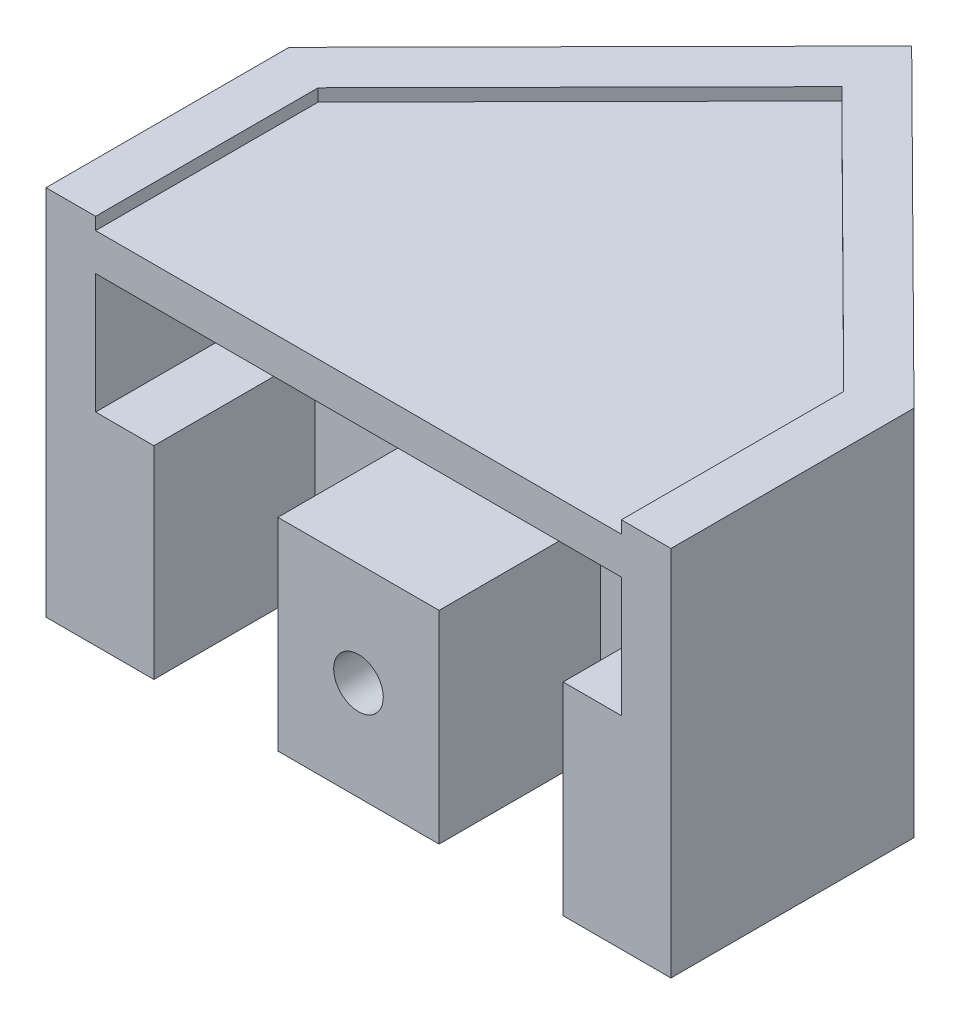
SolidWorks part; units mm, degrees
ref_plane "Plan de face" through (0, 0, 0) normal (0, 0, 1) x (1, 0, 0)
ref_plane "Plan de dessus" through (0, 0, 0) normal (0, 1, 0) x (1, 0, 0)
ref_plane "Plan de droite" through (0, 0, 0) normal (1, 0, 0) x (0, 0, -1)
sketch "Sketch2" plane through (0, 0, 0) normal (0, 0, 1) x (1, 0, 0)
  line L1 (0, 0) -> (-25.2, 0)
  line L2 (0, 0) -> (0, 15)
  line L3 (0, 15) -> (-25.2, 15)
  line L4 (-25.2, 0) -> (-25.2, 15)
  dimension "D1" = 25.2
  dimension "D2" = 15
extrude "Boss-Extrude2" add sketch "Sketch2" along normal blind 2
sketch "Sketch3" plane through (0, 0, 2) normal (0, 0, 1) x (1, 0, 0)
  line L0 (0, 15) -> (-25.2, 15) construction
  line L1 (-25.2, 0) -> (-23.2, 0)
  line L2 (-25.2, 0) -> (-25.2, 15)
  line L3 (-25.2, 15) -> (-23.2, 15)
  line L4 (-23.2, 0) -> (-23.2, 15)
  line L6 (-23.2, 13) -> (0, 13)
  line L7 (-23.2, 13) -> (-23.2, 15)
  line L8 (-23.2, 15) -> (0, 15)
  line L9 (0, 13) -> (0, 15)
  line L10 (0, 0) -> (-2, 0)
  line L11 (0, 0) -> (0, 13)
  line L12 (0, 13) -> (-2, 13)
  line L13 (-2, 0) -> (-2, 13)
  line M4 (0, 0) -> (0, 15)
  line M5 (0, 15) -> (-25.2, 15)
  line M6 (-25.2, 15) -> (-25.2, 0)
  line M7 (-25.2, 0) -> (0, 0)
  dimension "D1" = 2
  dimension "D2" = 2
  dimension "D3" = 2
extrude "Boss-Extrude3" add sketch "Sketch3" along normal blind 7.8 contours L4 M7 M5 M6 | L4 L6 M4 M5 | L13 L6 M7 M4
sketch "Sketch4" plane through (0, 15, 0) normal (0, 1, 0) x (1, 0, 0)
  line L0 (0, 0) -> (-12.6933, 12.5997) construction
  line L1 (-25.2, 0) -> (-12.6933, 12.5997) construction
  line L2 (0, 0) -> (-12.6933, 12.5997)
  line L3 (-12.6933, 12.5997) -> (-25.2, 0)
  line L4 (-25.2, 0) -> (0, 0)
extrude "Boss-Extrude4" add sketch "Sketch4" against normal through all
sketch "Sketch5" plane through (0, 0, 2) normal (0, 0, 1) x (1, 0, 0)
  line L0 (-23.2, 0) -> (-2, 0) construction
  line L1 (-20.85, 0) -> (-4.35, 0)
  line L2 (-20.85, 0) -> (-20.85, 8.1631)
  line L3 (-20.85, 8.1631) -> (-4.35, 8.1631)
  line L4 (-4.35, 0) -> (-4.35, 8.1631)
  line L5 (-20.1, 6) -> (-20.1, 8.5) construction
  line L7 (-2, 0) -> (-2, 13) construction
  line L8 (-23.2, 0) -> (-2, 0)
  line L9 (-23.2, 0) -> (-23.2, 8.1631)
  line L10 (-23.2, 8.1631) -> (-2, 8.1631)
  line L11 (-2, 0) -> (-2, 8.1631)
  line L12 (-17.6, 6) -> (-17.6, 8.5) construction
  line L13 (-15.85, 0) -> (-9.35, 0)
  line L14 (-15.85, 0) -> (-15.85, 8.1631)
  line L15 (-15.85, 8.1631) -> (-9.35, 8.1631)
  line L16 (-9.35, 0) -> (-9.35, 8.1631)
  line M7 (-23.2, 0) -> (-2, 0)
  line M8 (-2, 0) -> (-2, 13)
  line M10 (-23.2, 13) -> (-23.2, 0)
  dimension "D1" = 16.5
  dimension "D2" = 0.75
  dimension "D3" = 0
  dimension "D4" = 6.5
  dimension "D5" = 1.75
extrude "Boss-Extrude5" add sketch "Sketch5" along normal blind 7.8 contours L8 L16 L10 L14 | L10 L4 M7 M8 | L10 L2 M10 M7
sketch "Sketch6" plane through (0, 0, 2) normal (0, 0, 1) x (1, 0, 0)
  line L1 (-20.85, 0) -> (-15.85, 0)
  line L2 (-20.85, 0) -> (-20.85, 8.1631)
  line L3 (-20.85, 8.1631) -> (-15.85, 8.1631)
  line L4 (-15.85, 0) -> (-15.85, 8.1631)
  line L5 (-9.35, 0) -> (-4.35, 0)
  line L6 (-9.35, 0) -> (-9.35, 8.1631)
  line L7 (-9.35, 8.1631) -> (-4.35, 8.1631)
  line L8 (-4.35, 0) -> (-4.35, 8.1631)
extrude "Boss-Extrude6" add sketch "Sketch6" along normal blind 1.3
sketch "Sketch8" plane through (0, 15, 0) normal (0, 1, 0) x (1, 0, 0)
  line L6 (-23.2, -7.8) -> (-2, -7.8)
  line L7 (-23.2, -7.8) -> (-23.2, -9.8)
  line L8 (-23.2, -9.8) -> (-2, -9.8)
  line L9 (-2, -7.8) -> (-2, -9.8)
  line L10 (-2, -7.8) -> (-2, -0.8328)
  line L11 (-2, -0.8328) -> (-12.6829, 9.7712)
  line L12 (-12.6829, 9.7712) -> (-23.2, -0.8241)
  line L13 (-23.2, -0.8241) -> (-23.2, -7.8)
  line L14 (-23.2, -7.8) -> (-2, -7.8)
  line L15 (-2, -7.8) -> (-2, -0.8328)
  line L16 (-2, -0.8328) -> (-12.6829, 9.7712)
  line L17 (-12.6829, 9.7712) -> (-23.2, -0.8241)
  line L18 (-23.2, -0.8241) -> (-23.2, -7.8)
  line L19 (-23.2, -7.8) -> (-2, -7.8)
  line M10 (-25.2, -9.8) -> (0, -9.8)
  dimension "D1" = 2
extrude "Cut-Extrude1" cut sketch "Sketch8" against normal blind 0.5 contours L17 L18 L6 L15 L16 | L9 L6 L7 M10
sketch "Sketch10" plane through (0, 0, 9.8) normal (0, 0, 1) x (1, 0, 0)
  circle A0 centre (-12.6, 4) radius 1
extrude "Cut-Extrude4" cut sketch "Sketch10" along direction (0, 0, 1) on the side against the normal blind 6
